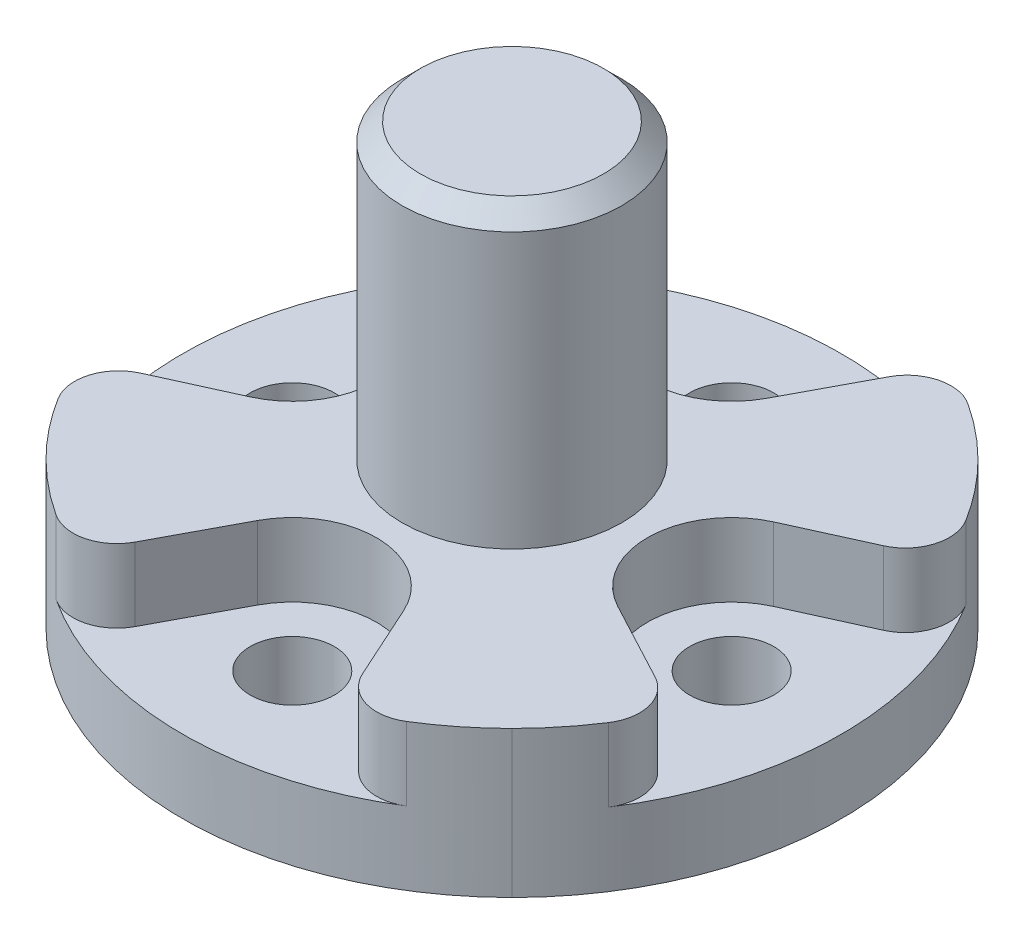
SolidWorks part; units mm, degrees
ref_plane "前视基准面" through (0, 0, 0) normal (0, 0, 1) x (1, 0, 0)
ref_plane "上视基准面" through (0, 0, 0) normal (0, 1, 0) x (1, 0, 0)
ref_plane "右视基准面" through (0, 0, 0) normal (1, 0, 0) x (0, 0, -1)
other "Configuration Table"
sketch "草图1" plane through (0, 0, 0) normal (0, 1, 0) x (1, 0, 0)
  line L0 (0, 5.6648) -> (0, 0) construction
  line L1 (0, 0) -> (6.4446, 0) construction
  circle A0 centre (0, 0) radius 9
  circle A1 centre (6, 0) radius 1.15
  circle A2 centre (0.001, 0.001) radius 9
  circle A3 centre (0, 0.002) radius 9
  circle A4 centre (-0.001, 0.001) radius 9
  circle A5 centre (0, -6) radius 1.15
  circle A6 centre (-6, 0) radius 1.15
  circle A7 centre (0, 6) radius 1.15
  point P16 (0, 0.001)
  point P23 (0, 0)
  dimension "D1" = 18
  dimension "D2" = 2.3
  dimension "D5" = 12
  dimension "D3" = 4
  dimension "D4" = 4
extrude "凸台-拉伸1" add sketch "草图1" along normal blind 4
sketch "草图2" plane through (0, 4, 0) normal (0, 1, 0) x (1, 0, 0)
  circle A0 centre (0, 0) radius 3
  dimension "D1" = 6
extrude "凸台-拉伸2" add sketch "草图2" along normal blind 8
chamfer "倒角1" distance 0.5 angle 45 1 edges at (0, 12, 3)
sketch "草图4" plane through (0, 4, 0) normal (0, 1, 0) x (1, 0, 0)
  line L0 (5.0496, 2.0945) -> (8.2682, 3.5549)
  line L1 (4.9193, -2.0303) -> (8.1754, -3.7635)
  line L2 (2.0945, -5.0496) -> (3.5549, -8.2682)
  line L3 (-2.0303, -4.9193) -> (-3.7635, -8.1754)
  line L4 (-5.0496, -2.0945) -> (-8.2682, -3.5549)
  line L5 (-4.9193, 2.0303) -> (-8.1754, 3.7635)
  line L6 (-2.0945, 5.0496) -> (-3.5549, 8.2682)
  line L7 (2.0303, 4.9193) -> (3.7635, 8.1754)
  arc A0 (5.0496, 2.0945) -> (4.9193, -2.0303) centre (6, 0) ccw
  arc A1 (8.1754, -3.7635) -> (8.2682, 3.5549) centre (0, 0) ccw
  arc A2 (-3.7635, -8.1754) -> (3.5549, -8.2682) centre (0, 0) ccw
  arc A3 (2.0945, -5.0496) -> (-2.0303, -4.9193) centre (0, -6) ccw
  arc A4 (-8.1754, 3.7635) -> (-8.2682, -3.5549) centre (0, 0) ccw
  arc A5 (-5.0496, -2.0945) -> (-4.9193, 2.0303) centre (-6, 0) ccw
  arc A6 (3.7635, 8.1754) -> (-3.5549, 8.2682) centre (0, 0) ccw
  arc A7 (-2.0945, 5.0496) -> (2.0303, 4.9193) centre (0, 6) ccw
  point P26 (0, 0)
  dimension "D1" = 18
  dimension "D2" = 4.6
  dimension "D3" = 4
extrude "切除-拉伸2" cut sketch "草图4" against normal blind 2
fillet "圆角1" radius 1.2 8 edges at (-8.267, 3, 3.5543) (-3.7626, 3, 8.1737) (3.5541, 3, 8.2665) (8.1742, 3, 3.7628) (8.2677, 3, -3.5547) (3.7635, 3, -8.1754) (-3.5549, 3, -8.2682) (-8.1749, 3, -3.7632)
